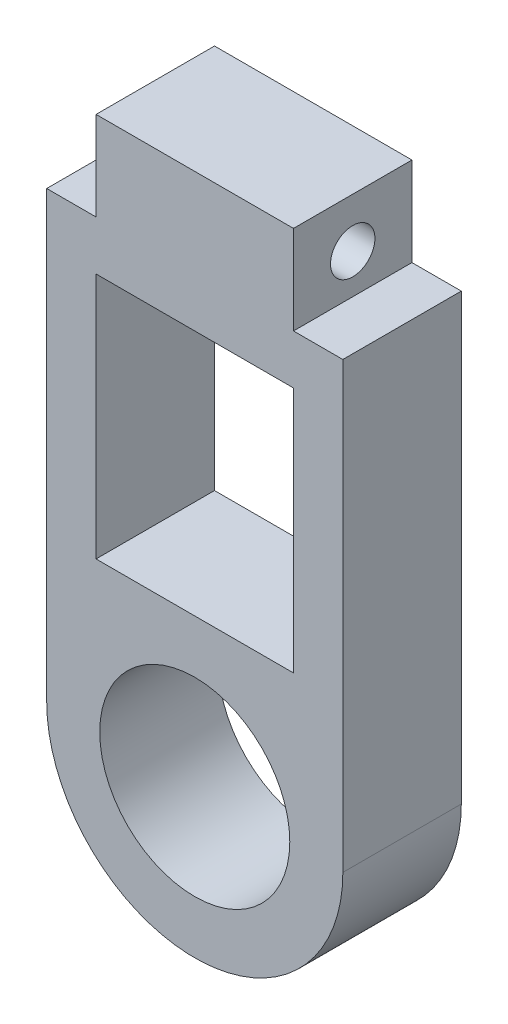
SolidWorks part; units mm, degrees
ref_plane "Front Plane" through (0, 0, 0) normal (0, 0, 1) x (1, 0, 0)
ref_plane "Top Plane" through (0, 0, 0) normal (0, 1, 0) x (1, 0, 0)
ref_plane "Right Plane" through (0, 0, 0) normal (1, 0, 0) x (0, 0, -1)
sketch "Sketch1" plane through (0, 0, 0) normal (0, 0, 1) x (1, 0, 0)
  line L0 (-10, -2.5059) -> (-10, 6.4941)
  line L1 (0, -55) -> (0, 55) construction
  line L2 (15, -2.5059) -> (15, -47.5059)
  line L3 (-15, -2.5059) -> (-15, -47.5059)
  line L4 (10, -2.5059) -> (15, -2.5059)
  line L5 (-10, 6.4941) -> (10, 6.4941)
  line L9 (-15, -2.5059) -> (-10, -2.5059)
  line L10 (0, -37.8809) -> (0, -47.5059) construction
  line L11 (10, 6.4941) -> (10, -2.5059)
  line L13 (-10, -7.5059) -> (10, -7.5059)
  line L14 (-10, -7.5059) -> (-10, -32.5059)
  line L15 (-10, -32.5059) -> (10, -32.5059)
  line L16 (10, -7.5059) -> (10, -32.5059)
  arc A1 (-15, -47.5059) -> (15, -47.5059) centre (0, -47.5059) ccw
  circle A3 centre (0, -47.5059) radius 9.625
  point P5 (0, 0)
  dimension "D3" = 10
  dimension "D6" = 19.25
  dimension "D1" = 20
  dimension "D2" = 9
  dimension "D4" = 25
  dimension "D5" = 15
extrude "Boss-Extrude1" add sketch "Sketch1" along normal blind 12
sketch "Sketch2" plane through (10, 0, 0) normal (1, 0, 0) x (0, 0, -1)
  line L1 (-12, -2.5059) -> (0, -2.5059) construction
  line L2 (-12, -2.5059) -> (-12, 6.4941) construction
  circle A0 centre (-6, 1.4941) radius 2.25
  dimension "D1" = 4
  dimension "D2" = 6
extrude "Cut-Extrude1" cut sketch "Sketch2" against normal through all
